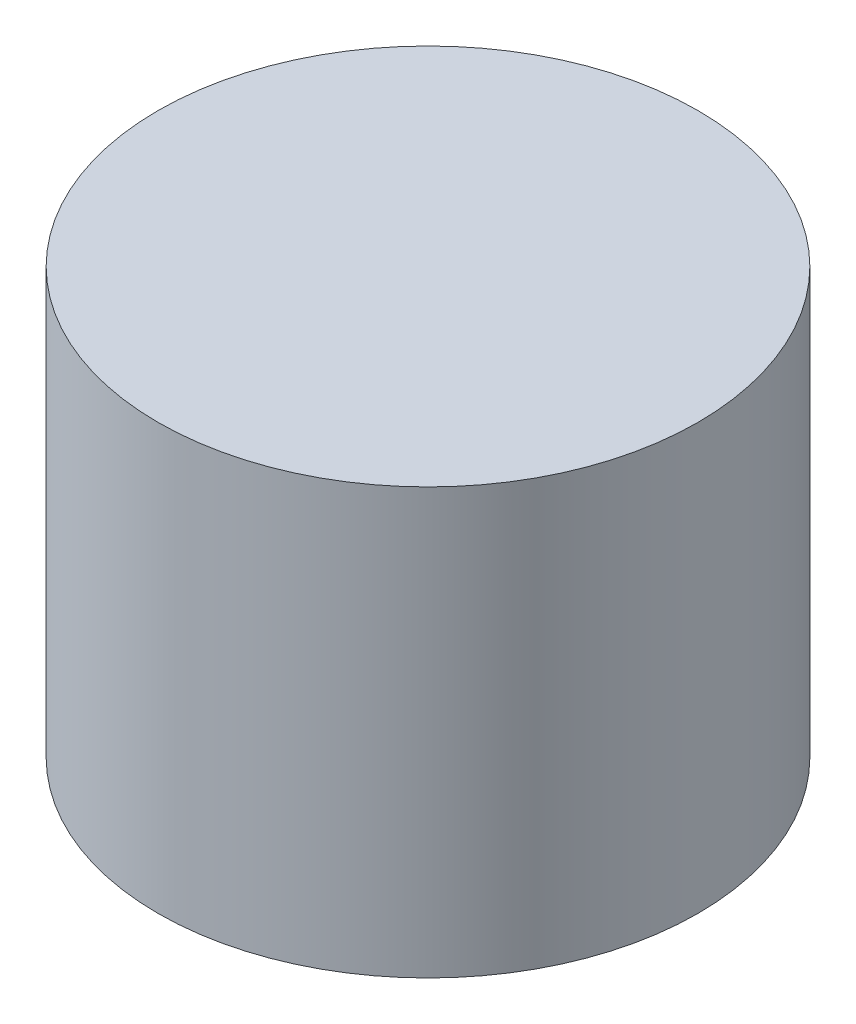
SolidWorks part; units mm, degrees
ref_plane "Front Plane" through (0, 0, 0) normal (0, 0, 1) x (1, 0, 0)
ref_plane "Top Plane" through (0, 0, 0) normal (0, 1, 0) x (1, 0, 0)
ref_plane "Right Plane" through (0, 0, 0) normal (1, 0, 0) x (0, 0, -1)
sketch "Sketch1" plane through (0, 0, 0) normal (0, 0, 1) x (1, 0, 0)
  line L0 (0, 0) -> (1, 0)
  line L1 (1, 0) -> (1, -1.52)
  line L2 (1, -1.52) -> (1.6, -1.52)
  line L3 (1.6, -1.52) -> (1.6, 1)
  line L4 (1.6, 1) -> (0, 1)
  line L5 (0, 1) -> (0, 0)
  dimension "D1" = 1.52
  dimension "D2" = 1.6
  dimension "D3" = 1
  dimension "D4" = 1
revolve "Revolve1" add sketch "Sketch1" angle 360 about L5
